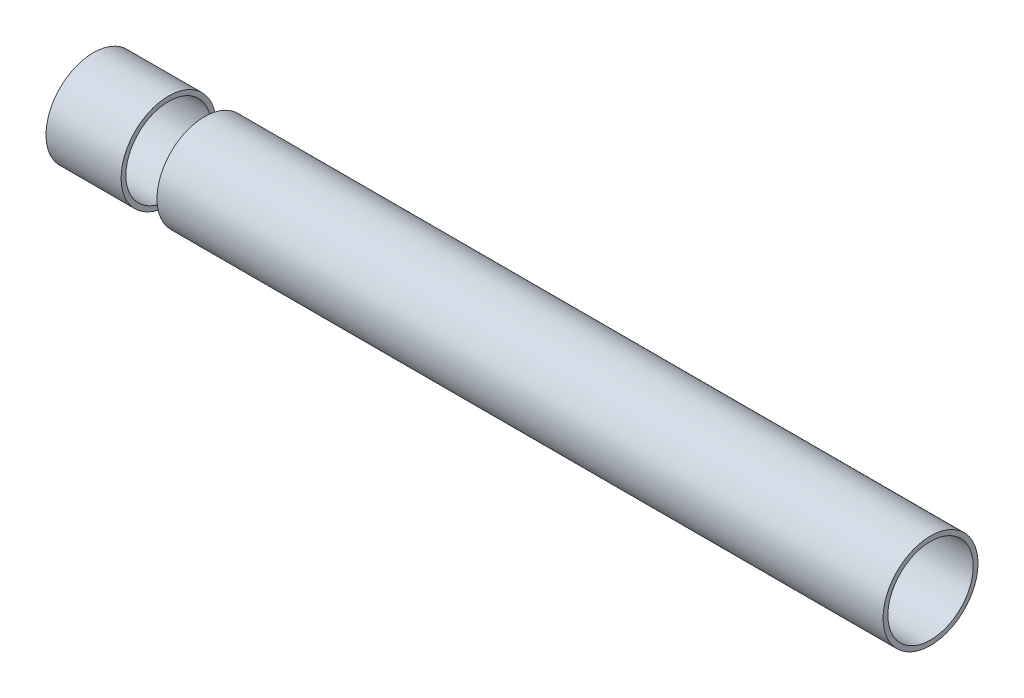
SolidWorks part; units mm, degrees
material "PC High Viscosity"
ref_plane "Front Plane" through (0, 0, 0) normal (0, 0, 1) x (1, 0, 0)
ref_plane "Top Plane" through (0, 0, 0) normal (0, 1, 0) x (1, 0, 0)
ref_plane "Right Plane" through (0, 0, 0) normal (1, 0, 0) x (0, 0, -1)
sketch "Sketch1" plane through (0, 0, 0) normal (1, 0, 0) x (0, 0, -1)
  circle A0 centre (0, 0) radius 15.875
  dimension "D1" = 31.75
extrude "Extrude-Thin1" add sketch "Sketch1" along normal mid plane 280.0385 thin thin type one direction reverse wall 1.5875
sketch "Sketch2" plane through (0, 0, 0) normal (0, 1, 0) x (1, 0, 0)
  line L0 (140.0193, 15.875) -> (-140.0193, 15.875) construction
  line L1 (-102.8953, 15.875) -> (-114.8953, 15.875)
  line L2 (-102.8953, 15.875) -> (-102.8953, -15.875)
  line L3 (-102.8953, -15.875) -> (-114.8953, -15.875)
  line L4 (-114.8953, 15.875) -> (-114.8953, -15.875)
  line L5 (-140.0193, -15.875) -> (140.0193, -15.875) construction
  line L6 (-140.0193, 14.2875) -> (-140.0193, -14.2875) construction
  dimension "D1" = 37.1239
  dimension "D2" = 12
extrude "Cut-Extrude1" cut sketch "Sketch2" against normal through all both and the other way through all
other "Save Bodies1"
equation "\"D2@Sketch2\"=12mm"
